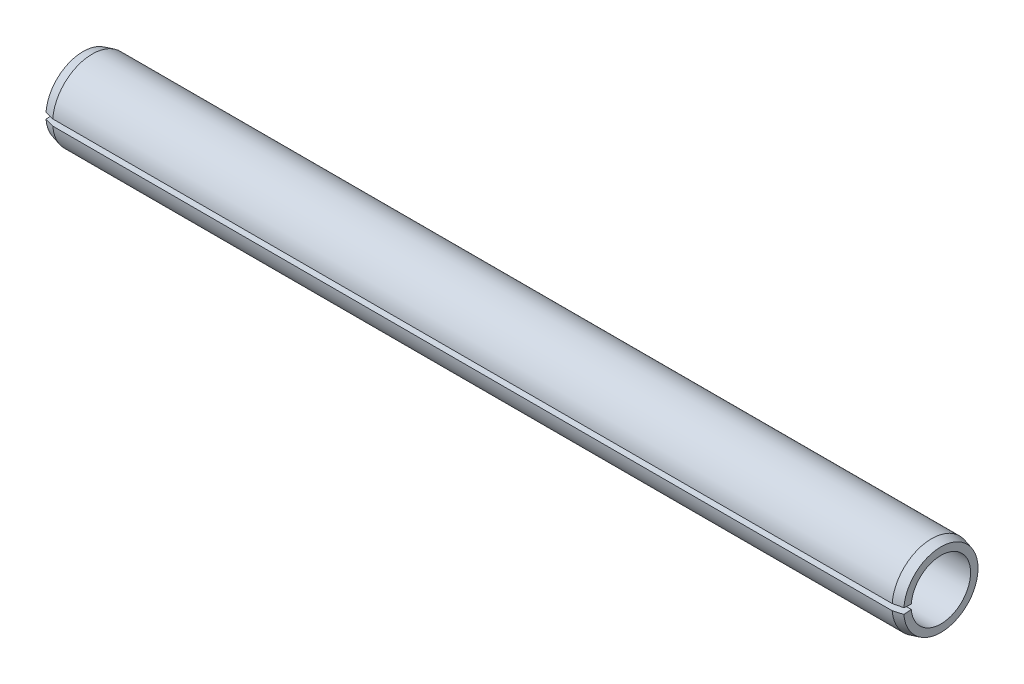
SolidWorks part; units mm, degrees
ref_plane "Plane1" through (0, 0, 0) normal (0, 0, 1) x (1, 0, 0)
ref_plane "Plane2" through (0, 0, 0) normal (0, 1, 0) x (1, 0, 0)
ref_plane "Plane3" through (0, 0, 0) normal (1, 0, 0) x (0, 0, -1)
other "Configuration Table"
sketch "Sketch1" plane through (0, 0, 0) normal (0, 0, 1) x (1, 0, 0)
  line L0 (-9.525, 0) -> (111.125, 0) construction
  line L1 (0, 2.25) -> (65, 2.25)
  line L2 (65, 2.25) -> (65, 2.8125)
  line L3 (65, 2.8125) -> (64.3, 3)
  line L4 (64.3, 3) -> (0.7, 3)
  line L5 (0.7, 3) -> (0, 2.8125)
  line L7 (0, 2.8125) -> (0, 2.25)
  dimension "D1" = 3.75
  dimension "D2" = 3.75
  dimension "D3" = 0.5
revolve "Base-Revolve" add sketch "Sketch1" angle 360 about L0
sketch "Sketch2" plane through (0, 0, 0) normal (-1, 0, 0) x (0, -1, 0)
  line L0 (0, 0) -> (0.2401, 3.0506)
  line L1 (0, -3.175) -> (0, 12.7) construction
  line L2 (0, 0) -> (-0.2401, 3.0506)
  arc A0 (0.2401, 3.0506) -> (-0.2401, 3.0506) centre (0, 0) ccw
  dimension "Gap_ang" = 9
  dimension "D1" = 2.04
extrude "Gap" cut sketch "Sketch2" against normal through all
equation "\"D1@Sketch2\" = \"Diameter@Sketch1\" * 0.51"
equation "\"D1@Sketch1\" = \"Diameter@Sketch1\" -  ( \"Thickness@Sketch1\" / 2 ) "
equation "\"D2@Sketch1\" = \"D1@Sketch1\""
equation "\"D3@Sketch1\" = \"Chamfer_len@Sketch1\""
